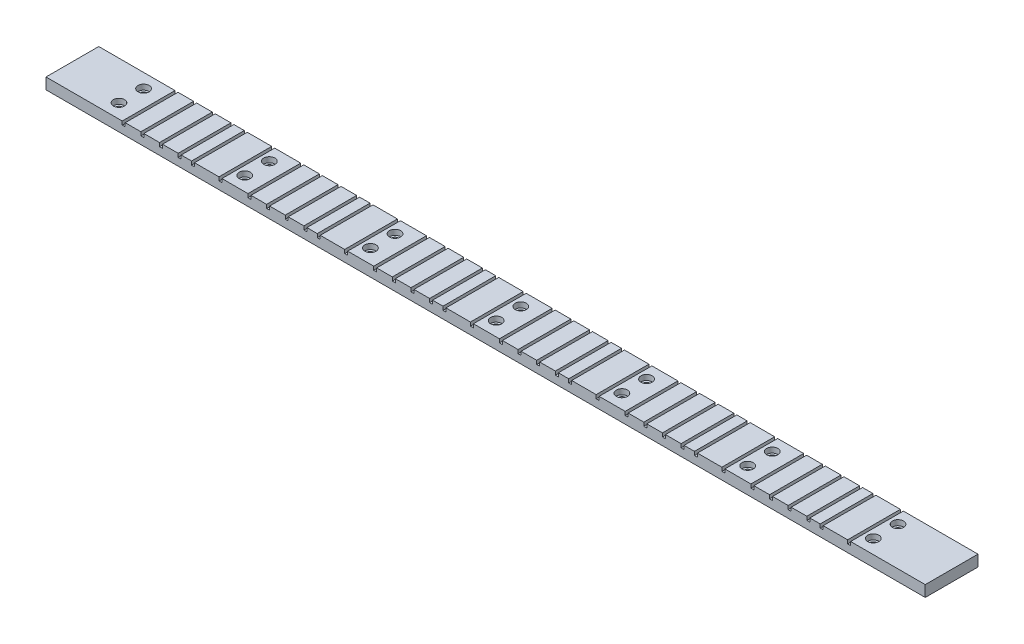
SolidWorks part; units mm, degrees
ref_plane "Front Plane" through (0, 0, 0) normal (0, 0, 1) x (1, 0, 0)
ref_plane "Top Plane" through (0, 0, 0) normal (0, 1, 0) x (1, 0, 0)
ref_plane "Right Plane" through (0, 0, 0) normal (1, 0, 0) x (0, 0, -1)
ref_plane "Plane1" through (0, 2, 0) normal (0, -1, 0) x (-1, 0, 0)
sketch "Sketch1" plane through (0, 2, 0) normal (0, -1, 0) x (-1, 0, 0)
  line L1 (100, 20) -> (-400, 20)
  line L2 (100, 20) -> (100, 50)
  line L3 (100, 50) -> (-400, 50)
  line L4 (-400, 20) -> (-400, 50)
extrude "Boss-Extrude1" add sketch "Sketch1" along normal blind 6.35
sketch "Sketch2" plane through (0, 2, 0) normal (0, -1, 0) x (1, 0, 0)
  circle A0 centre (5, -28) radius 3.175
  circle A1 centre (-66.5, -42) radius 3.175
  circle A2 centre (-66.5, -28) radius 3.175
  circle A3 centre (-66.5, -42) radius 3.175 construction
  circle A4 centre (-66.5, -28) radius 3.175 construction
  circle A5 centre (5, -42) radius 3.175
  circle A6 centre (76.5, -28) radius 3.175
  circle A7 centre (76.5, -42) radius 3.175
  circle A8 centre (148, -28) radius 3.175
  circle A9 centre (148, -42) radius 3.175
  circle A10 centre (219.5, -28) radius 3.175
  circle A11 centre (219.5, -42) radius 3.175
  circle A12 centre (291, -28) radius 3.175
  circle A13 centre (291, -42) radius 3.175
  circle A14 centre (362.5, -28) radius 3.175
  circle A15 centre (362.5, -42) radius 3.175
  dimension "D1" = 7
extrude "Cut-Extrude1" cut sketch "Sketch2" along normal blind 3
sketch "Sketch5" plane through (0, 0, -50) normal (0, 0, -1) x (-1, 0, 0)
  line L0 (-1.5747, 2.0001) -> (-0.0572, 2.0001)
  line L1 (-1.5747, 3.3668) -> (-1.5747, 2.0001)
  line L2 (61.7105, 3.3668) -> (-1.5747, 3.3668)
  line L3 (61.7105, 2.0001) -> (61.7105, 3.3668)
  line L4 (56.6446, -0.0571) -> (56.6446, 2.0001)
  line L5 (54.9428, 2.0001) -> (54.9428, -0.0571)
  line L6 (46.0446, 2.0001) -> (54.9428, 2.0001)
  line L7 (46.0446, -0.0571) -> (46.0446, 2.0001)
  line L8 (44.3428, -0.0571) -> (46.0446, -0.0571)
  line L9 (44.3428, 2.0001) -> (44.3428, -0.0571)
  line L10 (35.4446, 2.0001) -> (44.3428, 2.0001)
  line L11 (35.4446, -0.0571) -> (35.4446, 2.0001)
  line L12 (33.7428, -0.0571) -> (35.4446, -0.0571)
  line L174 (54.9428, -0.0571) -> (56.6446, -0.0571)
  line L181 (33.7428, 2.0001) -> (33.7428, -0.0571)
  line L182 (24.8446, 2.0001) -> (33.7428, 2.0001)
  line L183 (24.8446, -0.0571) -> (24.8446, 2.0001)
  line L184 (23.1428, -0.0571) -> (24.8446, -0.0571)
  line L185 (23.1428, 2.0001) -> (23.1428, -0.0571)
  line L186 (17.2446, 2.0001) -> (23.1428, 2.0001)
  line L187 (17.2446, -0.0571) -> (17.2446, 2.0001)
  line L188 (15.5428, -0.0571) -> (17.2446, -0.0571)
  line L189 (15.5428, 2.0001) -> (15.5428, -0.0571)
  line L190 (1.6446, 2.0001) -> (15.5428, 2.0001)
  line L191 (1.6446, -0.0571) -> (1.6446, 2.0001)
  line L192 (-0.0572, -0.0571) -> (1.6446, -0.0571)
  line L193 (-0.0572, 2.0001) -> (-0.0572, -0.0571)
  line L194 (-73.0747, 2.0001) -> (-71.5572, 2.0001)
  line L195 (-73.0747, 3.3668) -> (-73.0747, 2.0001)
  line L196 (-9.7895, 3.3668) -> (-73.0747, 3.3668)
  line L197 (-9.7895, 2.0001) -> (-9.7895, 3.3668)
  line L198 (-14.8554, 2.0001) -> (-9.7895, 2.0001)
  line L199 (-14.8554, -0.0571) -> (-14.8554, 2.0001)
  line L200 (-16.5572, -0.0571) -> (-14.8554, -0.0571)
  line L201 (-16.5572, 2.0001) -> (-16.5572, -0.0571)
  line L202 (-25.4554, 2.0001) -> (-16.5572, 2.0001)
  line L203 (-25.4554, -0.0571) -> (-25.4554, 2.0001)
  line L204 (-27.1572, -0.0571) -> (-25.4554, -0.0571)
  line L205 (-27.1572, 2.0001) -> (-27.1572, -0.0571)
  line L206 (-36.0554, 2.0001) -> (-27.1572, 2.0001)
  line L207 (-36.0554, -0.0571) -> (-36.0554, 2.0001)
  line L208 (-37.7572, -0.0571) -> (-36.0554, -0.0571)
  line L209 (-37.7572, 2.0001) -> (-37.7572, -0.0571)
  line L210 (-46.6554, 2.0001) -> (-37.7572, 2.0001)
  line L211 (-46.6554, -0.0571) -> (-46.6554, 2.0001)
  line L212 (-48.3572, -0.0571) -> (-46.6554, -0.0571)
  line L213 (-48.3572, 2.0001) -> (-48.3572, -0.0571)
  line L214 (-54.2554, 2.0001) -> (-48.3572, 2.0001)
  line L215 (-54.2554, -0.0571) -> (-54.2554, 2.0001)
  line L216 (-55.9572, -0.0571) -> (-54.2554, -0.0571)
  line L217 (-55.9572, 2.0001) -> (-55.9572, -0.0571)
  line L218 (-69.8554, 2.0001) -> (-55.9572, 2.0001)
  line L219 (-69.8554, -0.0571) -> (-69.8554, 2.0001)
  line L220 (-71.5572, -0.0571) -> (-69.8554, -0.0571)
  line L221 (-71.5572, 2.0001) -> (-71.5572, -0.0571)
  line L222 (-144.5747, 2.0001) -> (-143.0572, 2.0001)
  line L223 (-144.5747, 3.3668) -> (-144.5747, 2.0001)
  line L224 (-81.2895, 3.3668) -> (-144.5747, 3.3668)
  line L225 (-81.2895, 2.0001) -> (-81.2895, 3.3668)
  line L226 (-86.3554, 2.0001) -> (-81.2895, 2.0001)
  line L227 (-86.3554, -0.0571) -> (-86.3554, 2.0001)
  line L228 (-88.0572, -0.0571) -> (-86.3554, -0.0571)
  line L229 (-88.0572, 2.0001) -> (-88.0572, -0.0571)
  line L230 (-96.9554, 2.0001) -> (-88.0572, 2.0001)
  line L231 (-96.9554, -0.0571) -> (-96.9554, 2.0001)
  line L232 (-98.6572, -0.0571) -> (-96.9554, -0.0571)
  line L233 (-98.6572, 2.0001) -> (-98.6572, -0.0571)
  line L234 (-107.5554, 2.0001) -> (-98.6572, 2.0001)
  line L235 (-107.5554, -0.0571) -> (-107.5554, 2.0001)
  line L236 (-109.2572, -0.0571) -> (-107.5554, -0.0571)
  line L237 (-109.2572, 2.0001) -> (-109.2572, -0.0571)
  line L238 (-118.1554, 2.0001) -> (-109.2572, 2.0001)
  line L239 (-118.1554, -0.0571) -> (-118.1554, 2.0001)
  line L240 (-119.8572, -0.0571) -> (-118.1554, -0.0571)
  line L241 (-119.8572, 2.0001) -> (-119.8572, -0.0571)
  line L242 (-125.7554, 2.0001) -> (-119.8572, 2.0001)
  line L243 (-125.7554, -0.0571) -> (-125.7554, 2.0001)
  line L244 (-127.4572, -0.0571) -> (-125.7554, -0.0571)
  line L245 (-127.4572, 2.0001) -> (-127.4572, -0.0571)
  line L246 (-141.3554, 2.0001) -> (-127.4572, 2.0001)
  line L247 (-141.3554, -0.0571) -> (-141.3554, 2.0001)
  line L248 (-143.0572, -0.0571) -> (-141.3554, -0.0571)
  line L249 (-143.0572, 2.0001) -> (-143.0572, -0.0571)
  line L250 (-216.0747, 2.0001) -> (-214.5572, 2.0001)
  line L251 (-216.0747, 3.3668) -> (-216.0747, 2.0001)
  line L252 (-152.7895, 3.3668) -> (-216.0747, 3.3668)
  line L253 (-152.7895, 2.0001) -> (-152.7895, 3.3668)
  line L254 (-157.8554, 2.0001) -> (-152.7895, 2.0001)
  line L255 (-157.8554, -0.0571) -> (-157.8554, 2.0001)
  line L256 (-159.5572, -0.0571) -> (-157.8554, -0.0571)
  line L257 (-159.5572, 2.0001) -> (-159.5572, -0.0571)
  line L258 (-168.4554, 2.0001) -> (-159.5572, 2.0001)
  line L259 (-168.4554, -0.0571) -> (-168.4554, 2.0001)
  line L260 (-170.1572, -0.0571) -> (-168.4554, -0.0571)
  line L261 (-170.1572, 2.0001) -> (-170.1572, -0.0571)
  line L262 (-179.0554, 2.0001) -> (-170.1572, 2.0001)
  line L263 (-179.0554, -0.0571) -> (-179.0554, 2.0001)
  line L264 (-180.7572, -0.0571) -> (-179.0554, -0.0571)
  line L265 (-180.7572, 2.0001) -> (-180.7572, -0.0571)
  line L266 (-189.6554, 2.0001) -> (-180.7572, 2.0001)
  line L267 (-189.6554, -0.0571) -> (-189.6554, 2.0001)
  line L268 (-191.3572, -0.0571) -> (-189.6554, -0.0571)
  line L269 (-191.3572, 2.0001) -> (-191.3572, -0.0571)
  line L270 (-197.2554, 2.0001) -> (-191.3572, 2.0001)
  line L271 (-197.2554, -0.0571) -> (-197.2554, 2.0001)
  line L272 (-198.9572, -0.0571) -> (-197.2554, -0.0571)
  line L273 (-198.9572, 2.0001) -> (-198.9572, -0.0571)
  line L274 (-212.8554, 2.0001) -> (-198.9572, 2.0001)
  line L275 (-212.8554, -0.0571) -> (-212.8554, 2.0001)
  line L276 (-214.5572, -0.0571) -> (-212.8554, -0.0571)
  line L277 (-214.5572, 2.0001) -> (-214.5572, -0.0571)
  line L278 (-287.5747, 2.0001) -> (-286.0572, 2.0001)
  line L279 (-287.5747, 3.3668) -> (-287.5747, 2.0001)
  line L280 (-224.2895, 3.3668) -> (-287.5747, 3.3668)
  line L281 (-224.2895, 2.0001) -> (-224.2895, 3.3668)
  line L282 (-229.3554, 2.0001) -> (-224.2895, 2.0001)
  line L283 (-229.3554, -0.0571) -> (-229.3554, 2.0001)
  line L284 (-231.0572, -0.0571) -> (-229.3554, -0.0571)
  line L285 (-231.0572, 2.0001) -> (-231.0572, -0.0571)
  line L286 (-239.9554, 2.0001) -> (-231.0572, 2.0001)
  line L287 (-239.9554, -0.0571) -> (-239.9554, 2.0001)
  line L288 (-241.6572, -0.0571) -> (-239.9554, -0.0571)
  line L289 (-241.6572, 2.0001) -> (-241.6572, -0.0571)
  line L290 (-250.5554, 2.0001) -> (-241.6572, 2.0001)
  line L291 (-250.5554, -0.0571) -> (-250.5554, 2.0001)
  line L292 (-252.2572, -0.0571) -> (-250.5554, -0.0571)
  line L293 (-252.2572, 2.0001) -> (-252.2572, -0.0571)
  line L294 (-261.1554, 2.0001) -> (-252.2572, 2.0001)
  line L295 (-261.1554, -0.0571) -> (-261.1554, 2.0001)
  line L296 (-262.8572, -0.0571) -> (-261.1554, -0.0571)
  line L297 (-262.8572, 2.0001) -> (-262.8572, -0.0571)
  line L298 (-268.7554, 2.0001) -> (-262.8572, 2.0001)
  line L299 (-268.7554, -0.0571) -> (-268.7554, 2.0001)
  line L300 (-270.4572, -0.0571) -> (-268.7554, -0.0571)
  line L301 (-270.4572, 2.0001) -> (-270.4572, -0.0571)
  line L302 (-284.3554, 2.0001) -> (-270.4572, 2.0001)
  line L303 (-284.3554, -0.0571) -> (-284.3554, 2.0001)
  line L304 (-286.0572, -0.0571) -> (-284.3554, -0.0571)
  line L305 (-286.0572, 2.0001) -> (-286.0572, -0.0571)
  line L306 (-359.0747, 2.0001) -> (-357.5572, 2.0001)
  line L307 (-359.0747, 3.3668) -> (-359.0747, 2.0001)
  line L308 (-295.7895, 3.3668) -> (-359.0747, 3.3668)
  line L309 (-295.7895, 2.0001) -> (-295.7895, 3.3668)
  line L310 (-300.8554, 2.0001) -> (-295.7895, 2.0001)
  line L311 (-300.8554, -0.0571) -> (-300.8554, 2.0001)
  line L312 (-302.5572, -0.0571) -> (-300.8554, -0.0571)
  line L313 (-302.5572, 2.0001) -> (-302.5572, -0.0571)
  line L314 (-311.4554, 2.0001) -> (-302.5572, 2.0001)
  line L315 (-311.4554, -0.0571) -> (-311.4554, 2.0001)
  line L316 (-313.1572, -0.0571) -> (-311.4554, -0.0571)
  line L317 (-313.1572, 2.0001) -> (-313.1572, -0.0571)
  line L318 (-322.0554, 2.0001) -> (-313.1572, 2.0001)
  line L319 (-322.0554, -0.0571) -> (-322.0554, 2.0001)
  line L320 (-323.7572, -0.0571) -> (-322.0554, -0.0571)
  line L321 (-323.7572, 2.0001) -> (-323.7572, -0.0571)
  line L322 (-332.6554, 2.0001) -> (-323.7572, 2.0001)
  line L323 (-332.6554, -0.0571) -> (-332.6554, 2.0001)
  line L324 (-334.3572, -0.0571) -> (-332.6554, -0.0571)
  line L325 (-334.3572, 2.0001) -> (-334.3572, -0.0571)
  line L326 (-340.2554, 2.0001) -> (-334.3572, 2.0001)
  line L327 (-340.2554, -0.0571) -> (-340.2554, 2.0001)
  line L328 (-341.9572, -0.0571) -> (-340.2554, -0.0571)
  line L329 (-341.9572, 2.0001) -> (-341.9572, -0.0571)
  line L330 (-355.8554, 2.0001) -> (-341.9572, 2.0001)
  line L331 (-355.8554, -0.0571) -> (-355.8554, 2.0001)
  line L332 (-357.5572, -0.0571) -> (-355.8554, -0.0571)
  line L333 (-357.5572, 2.0001) -> (-357.5572, -0.0571)
  line L334 (56.6446, 2.0001) -> (61.7105, 2.0001)
extrude "Cut-Extrude2" cut sketch "Sketch5" against normal through all
sketch "Sketch6" plane through (0, -4.35, 0) normal (0, -1, 0) x (1, 0, 0)
  circle A0 centre (-66.5, -42) radius 1.8987
  circle A1 centre (-66.5, -28) radius 1.8987
  circle A3 centre (-66.5, -28) radius 1.8987 construction
  circle A4 centre (-66.5, -42) radius 1.8987 construction
  circle A5 centre (5, -42) radius 1.8987
  circle A6 centre (5, -28) radius 1.8987
  circle A7 centre (76.5, -42) radius 1.8987
  circle A8 centre (76.5, -28) radius 1.8987
  circle A9 centre (148, -42) radius 1.8987
  circle A10 centre (148, -28) radius 1.8987
  circle A11 centre (219.5, -42) radius 1.8987
  circle A12 centre (219.5, -28) radius 1.8987
  circle A13 centre (291, -42) radius 1.8987
  circle A14 centre (291, -28) radius 1.8987
  circle A15 centre (362.5, -42) radius 1.8987
  circle A16 centre (362.5, -28) radius 1.8987
  dimension "D1" = 7
extrude "Cut-Extrude3" cut sketch "Sketch6" against normal through all
